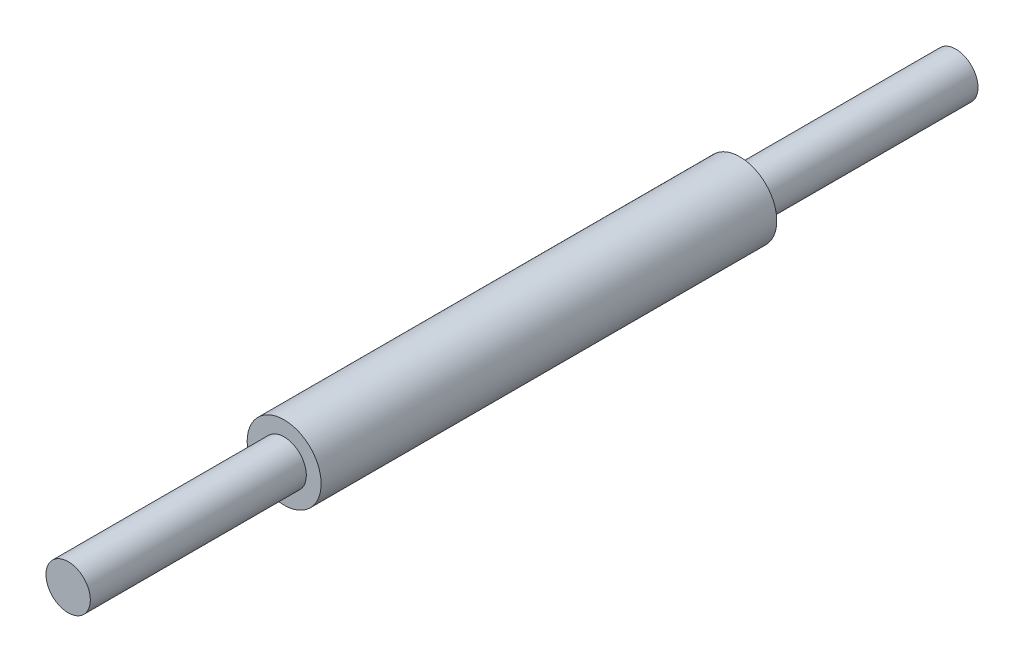
SolidWorks part; units mm, degrees
ref_plane "Front Plane" through (0, 0, 0) normal (0, 0, 1) x (1, 0, 0)
ref_plane "Top Plane" through (0, 0, 0) normal (0, 1, 0) x (1, 0, 0)
ref_plane "Right Plane" through (0, 0, 0) normal (1, 0, 0) x (0, 0, -1)
sketch "Sketch1" plane through (0, 0, 0) normal (0, 0, 1) x (1, 0, 0)
  circle A0 centre (0, 0) radius 2.5
  dimension "D1" = 5
extrude "Boss-Extrude6" add sketch "Sketch1" along normal mid plane 30.8
sketch "Sketch5" plane through (0, 0, 0) normal (0, 0, 1) x (1, 0, 0)
  circle A0 centre (0, 0) radius 1.5
  dimension "D1" = 3
extrude "Boss-Extrude8" add sketch "Sketch5" along normal mid plane 60
